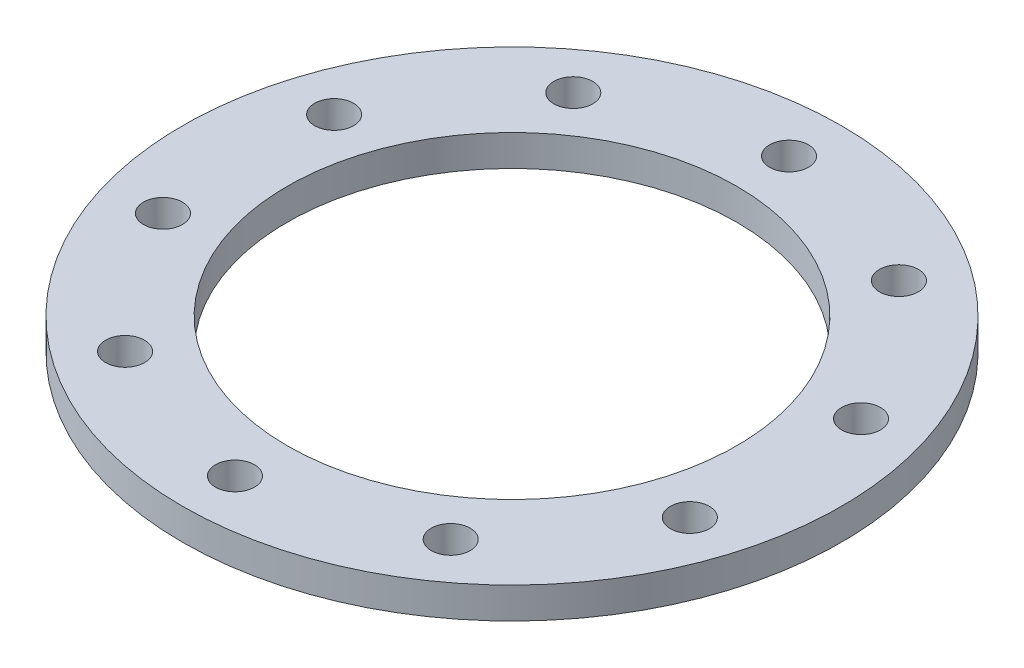
SolidWorks part; units mm, degrees
ref_plane "Front Plane" through (0, 0, 0) normal (0, 0, 1) x (1, 0, 0)
ref_plane "Top Plane" through (0, 0, 0) normal (0, 1, 0) x (1, 0, 0)
ref_plane "Right Plane" through (0, 0, 0) normal (1, 0, 0) x (0, 0, -1)
sketch "Sketch1" plane through (0, 0, 0) normal (0, 1, 0) x (1, 0, 0)
  circle A0 centre (0, 0) radius 45.789
  circle A1 centre (0, 0) radius 67.1332
extrude "Boss-Extrude1" add sketch "Sketch1" along normal blind 6.35
sketch "Sketch2" plane through (0, 6.35, 0) normal (0, 1, 0) x (1, 0, 0)
  circle A0 centre (0, 56.4286) radius 3.9688
  dimension "D1" = 7.9375
extrude "Cut-Extrude1" cut sketch "Sketch2" against normal up to next
pattern_circular "CirPattern1" count 10 over 360 about axis through (0, 0, 0) along (0, 1, 0) of "Cut-Extrude1"
